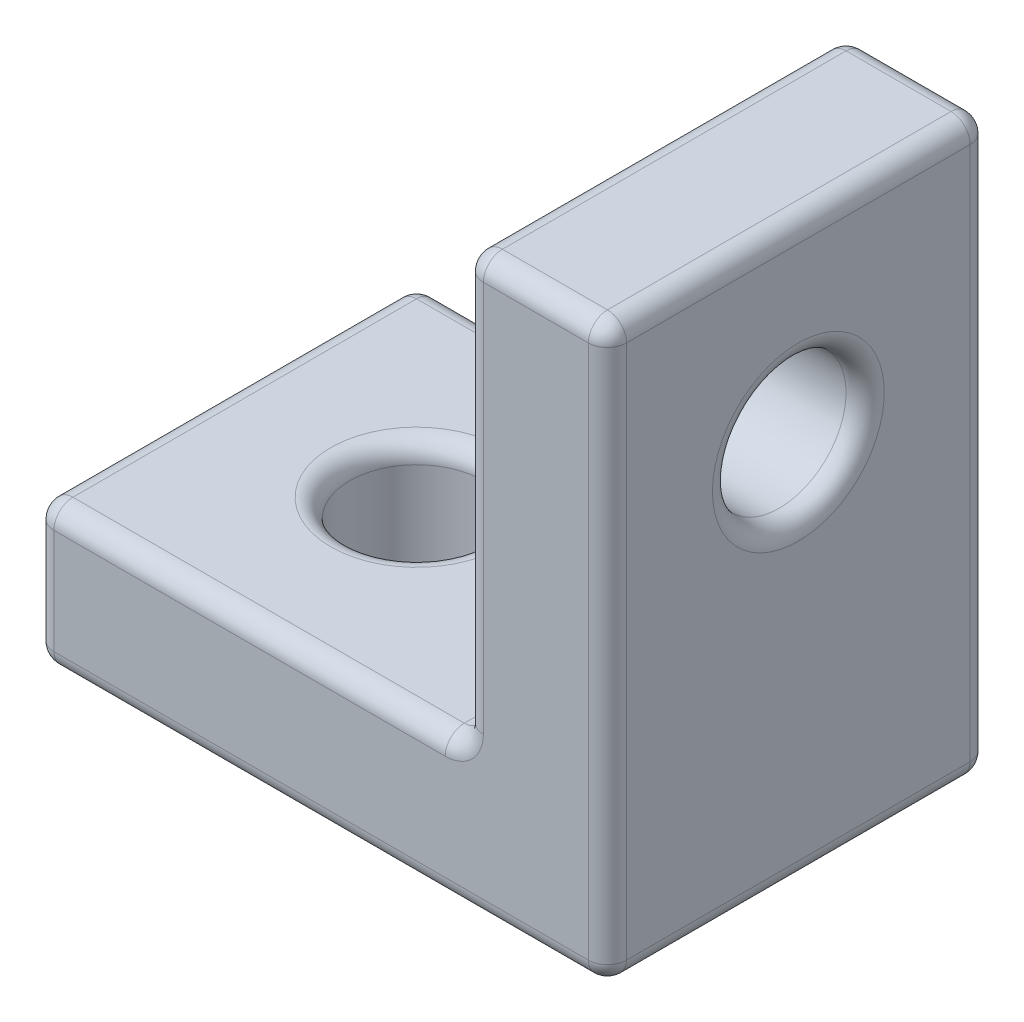
SolidWorks part; units mm, degrees
ref_plane "Front Plane" through (0, 0, 0) normal (0, 0, 1) x (1, 0, 0)
ref_plane "Top Plane" through (0, 0, 0) normal (0, 1, 0) x (1, 0, 0)
ref_plane "Right Plane" through (0, 0, 0) normal (1, 0, 0) x (0, 0, -1)
sketch "Sketch1" plane through (0, 0, 0) normal (0, 1, 0) x (1, 0, 0)
  line L1 (0, 0) -> (12, 0)
  line L2 (0, 0) -> (0, -8)
  line L3 (0, -8) -> (12, -8)
  line L4 (12, 0) -> (12, -8)
  circle A0 centre (4, -4) radius 1.4
  dimension "D1" = 2.8
  dimension "D2" = 8
  dimension "D3" = 4
  dimension "D4" = 4
  dimension "D5" = 12
extrude "Boss-Extrude1" add sketch "Sketch1" along normal blind 3
sketch "Sketch2" plane through (0, 3, 0) normal (0, 1, 0) x (1, 0, 0)
  line L0 (0, -8) -> (12, -8) construction
  line L1 (12, 0) -> (9, 0)
  line L2 (12, 0) -> (12, -8)
  line L3 (12, -8) -> (9, -8)
  line L4 (9, 0) -> (9, -8)
  dimension "D1" = 3
extrude "Boss-Extrude2" add sketch "Sketch2" along normal blind 9
sketch "Sketch3" plane through (9, 0, 0) normal (-1, 0, 0) x (0, 0, 1)
  line L0 (8, 12) -> (8, 3) construction
  line L1 (0, 3) -> (8, 3) construction
  circle A0 centre (4, 8) radius 1.4
  dimension "D1" = 2.8
  dimension "D2" = 4
  dimension "D3" = 5
extrude "Cut-Extrude1" cut sketch "Sketch3" against normal blind 10
fillet "Fillet1" radius 0.4 22 edges at (12, 8, 5.4) (4, 0, 5.4) (12, 0, 4) (12, 6, 8) (6, 0, 8) (0, 1.5, 8) (0, 0, 4) (4, 3, 5.4) (4.5, 3, 8) (0, 3, 4) (9, 7.5, 8) (9, 3, 4) (9, 8, 5.4) (10.5, 12, 8) (9, 12, 4) (12, 12, 4) (12, 6, 0) (10.5, 12, 0) (9, 7.5, 0) (4.5, 3, 0) (0, 1.5, 0) (6, 0, 0)
